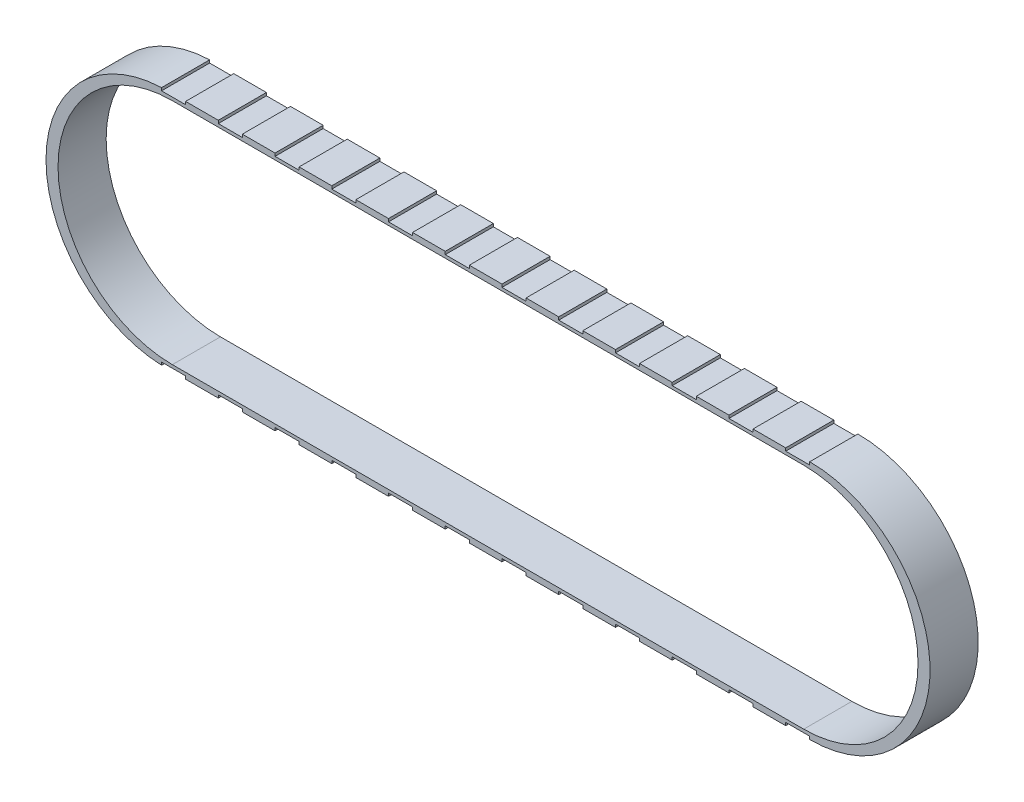
SolidWorks part; units mm, degrees
ref_plane "Front Plane" through (0, 0, 0) normal (0, 0, 1) x (1, 0, 0)
ref_plane "Top Plane" through (0, 0, 0) normal (0, 1, 0) x (1, 0, 0)
ref_plane "Right Plane" through (0, 0, 0) normal (1, 0, 0) x (0, 0, -1)
sketch "Sketch11" plane through (0, 0, 0) normal (0, 0, 1) x (1, 0, 0)
  line L0 (-84.8995, 0) -> (84.8995, 0) construction
  line L1 (-84.8995, 31.75) -> (84.8995, 31.75)
  line L2 (-84.8995, -31.75) -> (84.8995, -31.75)
  arc A0 (-84.8995, 31.75) -> (-84.8995, -31.75) centre (-84.8995, 0) ccw
  arc A1 (84.8995, -31.75) -> (84.8995, 31.75) centre (84.8995, 0) ccw
  point P2 (0, 0)
extrude "Boss-Extrude4" add sketch "Sketch11" along normal blind 12.7
sketch "Sketch12" plane through (0, 0, 12.7) normal (0, 0, 1) x (1, 0, 0)
  line L0 (-83.312, 0) -> (83.312, 0) construction
  line L1 (-83.312, 30.1625) -> (83.312, 30.1625)
  line L2 (-83.312, -30.1625) -> (83.312, -30.1625)
  arc A0 (-83.312, 30.1625) -> (-83.312, -30.1625) centre (-83.312, 0) ccw
  arc A1 (83.312, -30.1625) -> (83.312, 30.1625) centre (83.312, 0) ccw
  point P2 (0, 0)
extrude "Cut-Extrude4" cut sketch "Sketch12" against normal blind 12.7
sketch "Sketch13" plane through (0, 0, 0) normal (0, 0, -1) x (-1, 0, 0)
  line L1 (-84.8995, 31.75) -> (-78.5495, 31.75)
  line L2 (-84.8995, 31.75) -> (-84.8995, 30.988)
  line L3 (-84.8995, 30.988) -> (-78.5495, 30.988)
  line L4 (-78.5495, 31.75) -> (-78.5495, 30.988)
extrude "Cut-Extrude5" cut sketch "Sketch13" against normal blind 12.7
pattern_linear "LPattern3" count 12 spacing 14.9733 along (-1, 0, 0) of "Cut-Extrude5"
sketch "Sketch14" plane through (0, 0, 0) normal (0, 0, -1) x (-1, 0, 0)
  line L1 (-84.8995, -31.75) -> (-78.5495, -31.75)
  line L2 (-84.8995, -31.75) -> (-84.8995, -30.988)
  line L3 (-84.8995, -30.988) -> (-78.5495, -30.988)
  line L4 (-78.5495, -31.75) -> (-78.5495, -30.988)
extrude "Cut-Extrude6" cut sketch "Sketch14" against normal blind 12.7
pattern_linear "LPattern4" count 12 spacing 14.9733 along (-1, 0, 0) of "Cut-Extrude6"
